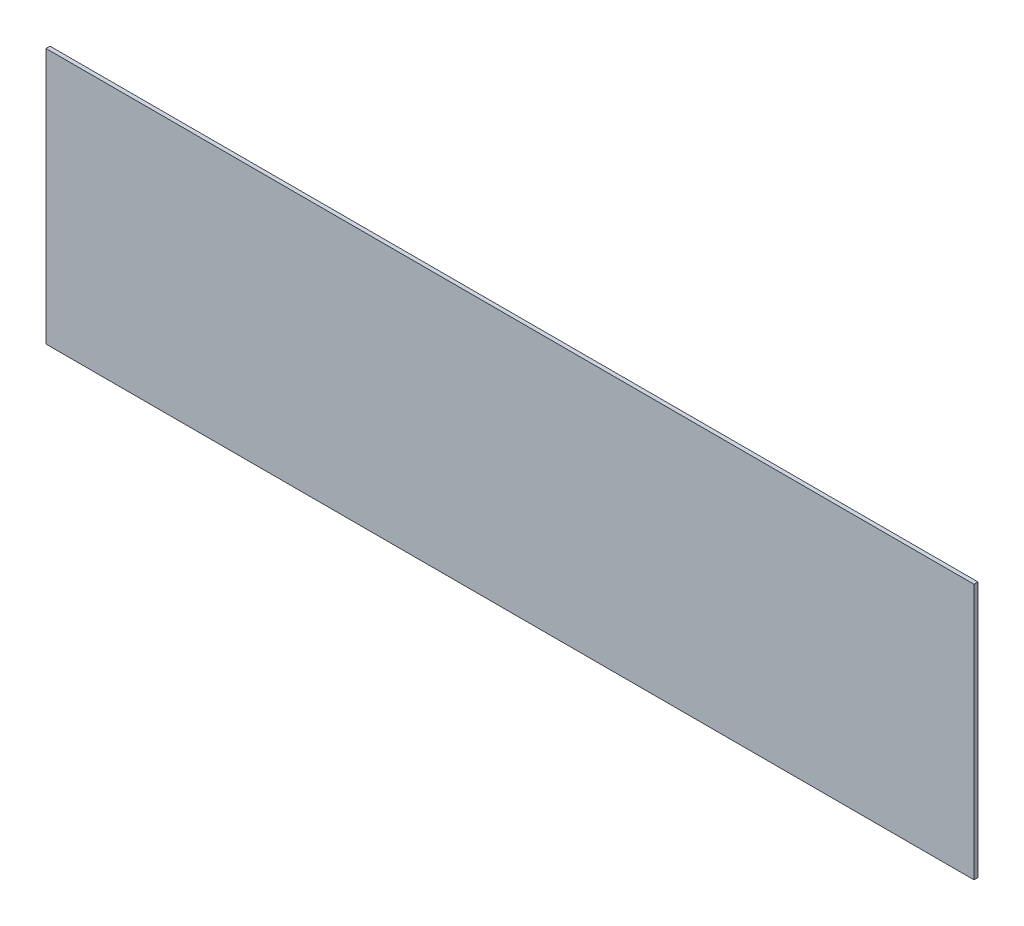
SolidWorks part; units mm, degrees
ref_plane "Front Plane" through (0, 0, 0) normal (0, 0, 1) x (1, 0, 0)
ref_plane "Top Plane" through (0, 0, 0) normal (0, 1, 0) x (1, 0, 0)
ref_plane "Right Plane" through (0, 0, 0) normal (1, 0, 0) x (0, 0, -1)
sketch "Sketch1" plane through (0, 0, 0) normal (0, 0, 1) x (1, 0, 0)
  line L1 (-368.3, -101.6) -> (368.3, -101.6)
  line L2 (-368.3, -101.6) -> (-368.3, 101.6)
  line L3 (-368.3, 101.6) -> (368.3, 101.6)
  line L4 (368.3, -101.6) -> (368.3, 101.6)
  line L5 (-368.3, -101.6) -> (368.3, 101.6) construction
  line L6 (-368.3, 101.6) -> (368.3, -101.6) construction
  point P0 (0, 0)
  dimension "D1" = 203.2
  dimension "D2" = 736.6
extrude "Boss-Extrude1" add sketch "Sketch1" along normal blind 3.175
